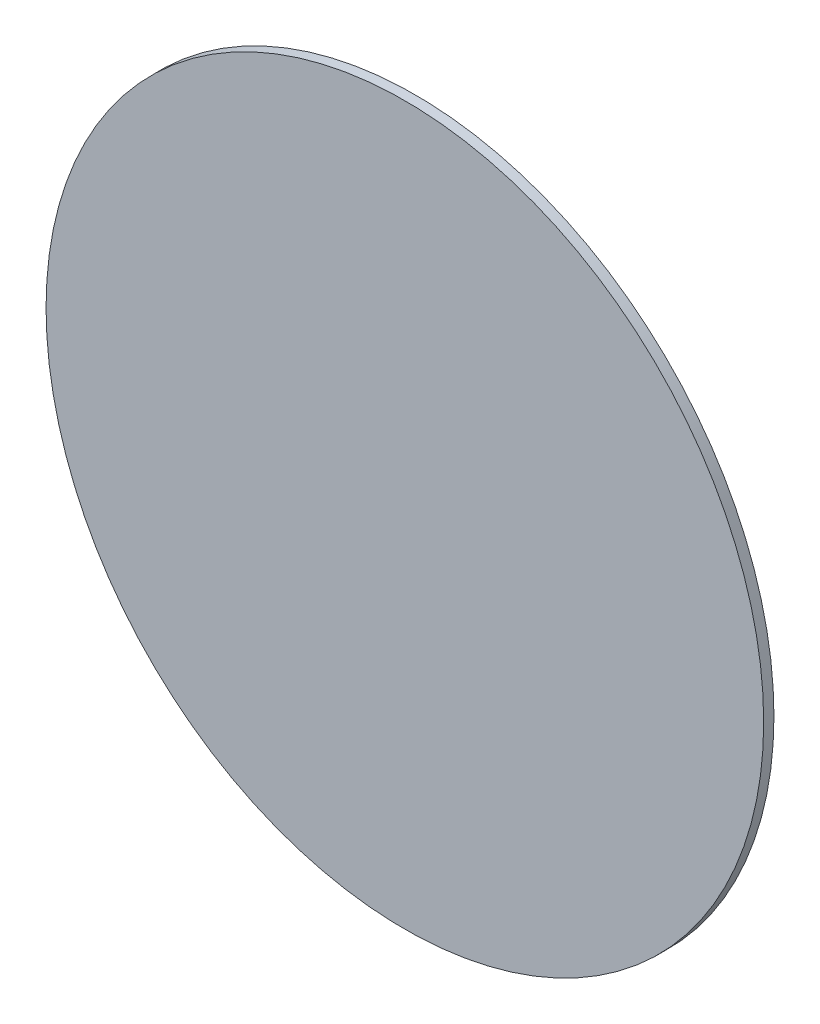
SolidWorks part; units mm, degrees
material "Balsa"
ref_plane "Plan de face" through (0, 0, 0) normal (0, 0, 1) x (1, 0, 0)
ref_plane "Plan de dessus" through (0, 0, 0) normal (0, 1, 0) x (1, 0, 0)
ref_plane "Plan de droite" through (0, 0, 0) normal (1, 0, 0) x (0, 0, -1)
sketch "Esquisse1" plane through (0, 0, 0) normal (0, 0, 1) x (1, 0, 0)
  circle A0 centre (0, 0) radius 175
extrude "Boss.-Extru.1" add sketch "Esquisse1" along normal blind 5
